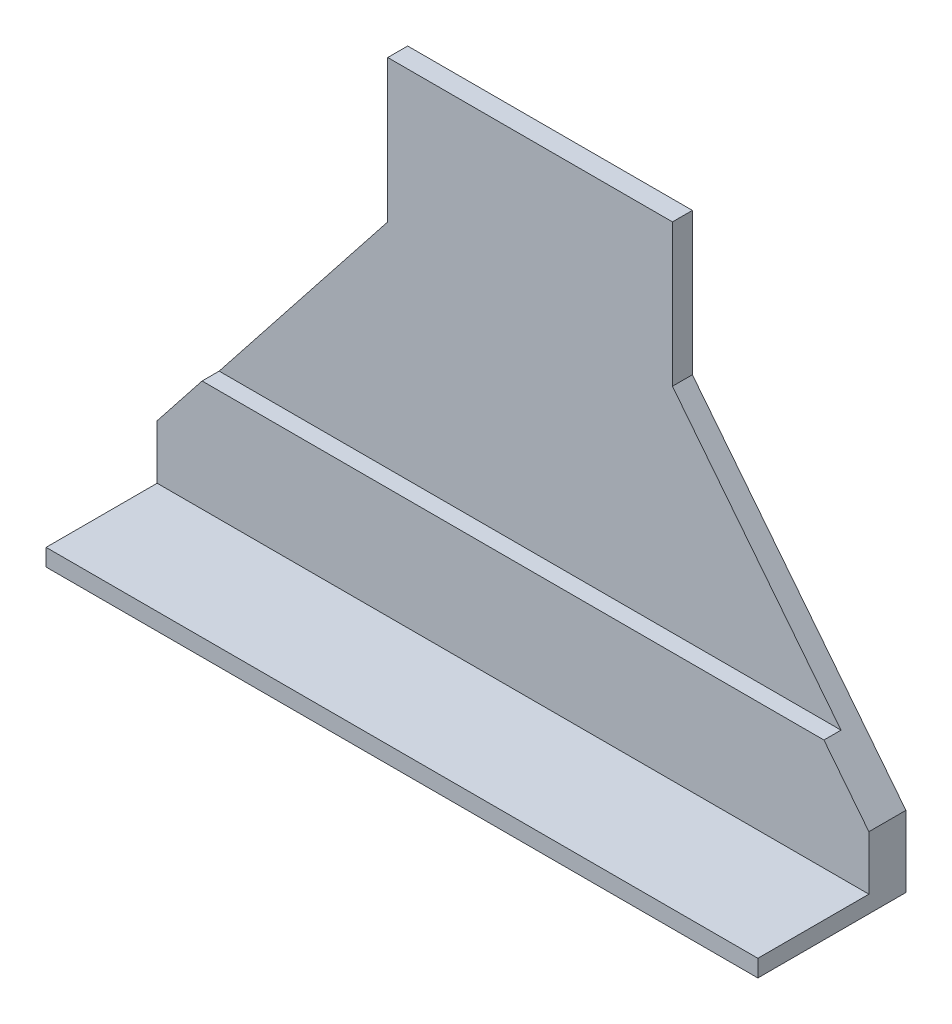
SolidWorks part; units mm, degrees
ref_plane "前视基准面" through (0, 0, 0) normal (0, 0, 1) x (1, 0, 0)
ref_plane "上视基准面" through (0, 0, 0) normal (0, 1, 0) x (1, 0, 0)
ref_plane "右视基准面" through (0, 0, 0) normal (1, 0, 0) x (0, 0, -1)
sketch "草图1" plane through (0, 0, 0) normal (0, 0, 1) x (1, 0, 0)
  line L1 (0, 0) -> (250, 0)
  line L2 (0, 0) -> (-250, 0)
  line L3 (-250, 0) -> (-250, 50)
  line L4 (250, 0) -> (250, 50)
  line L5 (0, 340) -> (100, 340)
  line L6 (0, 340) -> (-100, 340)
  line L7 (-100, 340) -> (-100, 240)
  line L8 (100, 340) -> (100, 240)
  line L9 (-100, 240) -> (-250, 50)
  line L10 (100, 240) -> (250, 50)
  dimension "D1" = 250
extrude "凸台-拉伸1" add sketch "草图1" along normal blind 14
sketch "草图2" plane through (0, 0, 14) normal (0, 0, 1) x (1, 0, 0)
  line L0 (-100, 290) -> (100, 290) construction
  line L1 (-100, 340) -> (-100, 240) construction
  line L2 (100, 240) -> (100, 340) construction
  line L3 (100, 340) -> (-100, 340) construction
  line L4 (0, 340) -> (0, 0) construction
  line L5 (-250, 50) -> (-250, 0) construction
  line L6 (-56, 340) -> (-56, 0) construction
  line L7 (-250, 0) -> (250, 0) construction
  dimension "D1" = 50
  dimension "D2" = 250
  dimension "D3" = 56
sketch "草图6" plane through (0, 0, 14) normal (0, 0, 1) x (1, 0, 0)
  line L0 (-218.4211, 90) -> (218.4211, 90) construction
  line L1 (-100, 240) -> (-250, 50) construction
  line L2 (250, 50) -> (100, 240) construction
  line L3 (-250, 0) -> (250, 0) construction
  dimension "D1" = 90
extrude "凸台-拉伸2" add sketch "草图6" along normal blind 12
sketch "草图8" plane through (0, 0, 26) normal (0, 0, 1) x (1, 0, 0)
  line L1 (-250, 0) -> (250, 0)
  line L2 (-250, 0) -> (-250, 12)
  line L3 (-250, 12) -> (250, 12)
  line L4 (250, 0) -> (250, 12)
extrude "凸台-拉伸5" add sketch "草图8" along normal blind 78
